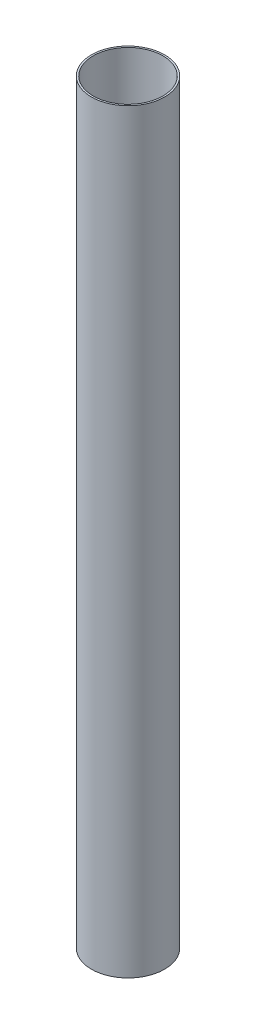
SolidWorks part; units mm, degrees
material "LE Phenolic"
ref_plane "Front Plane" through (0, 0, 0) normal (0, 0, 1) x (1, 0, 0)
ref_plane "Top Plane" through (0, 0, 0) normal (0, 1, 0) x (1, 0, 0)
ref_plane "Right Plane" through (0, 0, 0) normal (1, 0, 0) x (0, 0, -1)
sketch "Sketch1" plane through (0, 114.3, 0) normal (0, 1, 0) x (1, 0, 0)
  circle A0 centre (0, 0) radius 66.1924
  circle A1 centre (0, 0) radius 69.5071
  dimension "D1" = 139.0142
  dimension "D2" = 132.3848
extrude "Boss-Extrude1" add sketch "Sketch1" along normal blind 1434.592
